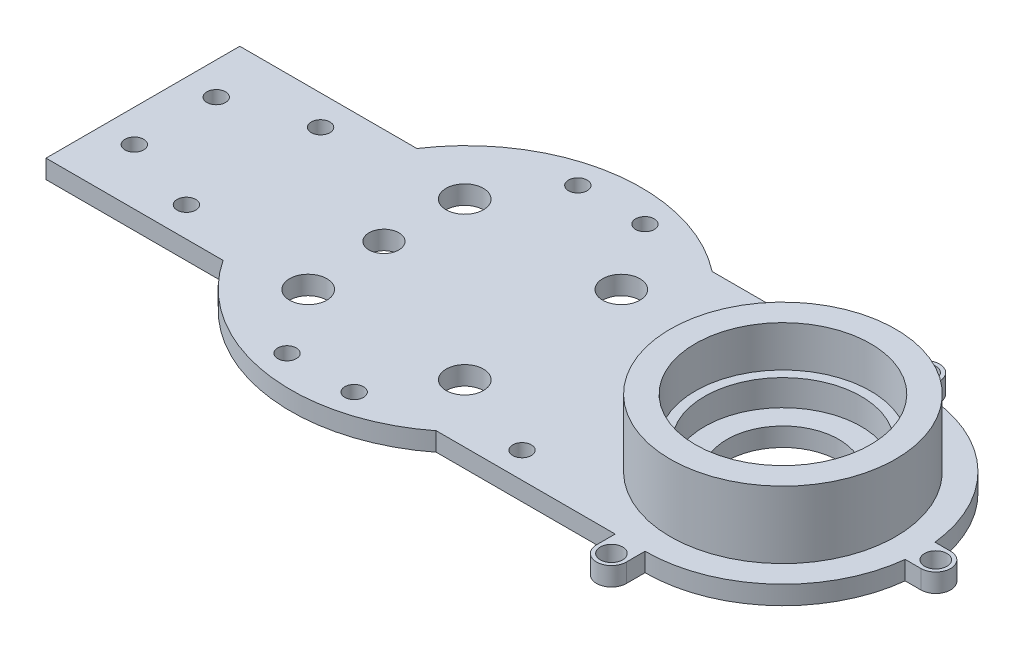
SolidWorks part; units mm, degrees
ref_plane "Front Plane" through (0, 0, 0) normal (0, 0, 1) x (1, 0, 0)
ref_plane "Top Plane" through (0, 0, 0) normal (0, 1, 0) x (1, 0, 0)
ref_plane "Right Plane" through (0, 0, 0) normal (1, 0, 0) x (0, 0, -1)
sketch "Sketch1" plane through (0, 0, 0) normal (0, 1, 0) x (1, 0, 0)
  line L0 (-72.9198, -40.4015) -> (-72.9198, 11.5785)
  line L1 (-72.9198, -40.4015) -> (-25.4198, -40.4015)
  line L2 (-72.9198, 11.5785) -> (-25.4198, 11.5785)
  line L3 (-72.9198, -40.4015) -> (-43.2498, -40.4015)
  line L12 (42.7452, 22.6085) -> (98.7452, 22.6085)
  line L13 (42.7502, -51.3915) -> (98.7452, -51.3915)
  line L14 (-72.9198, 11.5785) -> (-43.2498, 11.5785)
  line L22 (98.7452, 22.6085) -> (98.7452, 27.6085)
  line L23 (98.7452, -51.3915) -> (98.7452, -56.3899)
  line L24 (90.7452, 27.6085) -> (90.7452, 22.6085)
  line L25 (139.7485, -10.3958) -> (135.5288, -10.3958)
  line L26 (90.7452, -56.3899) -> (90.7452, -51.3915)
  line L28 (139.7485, -18.3872) -> (135.5288, -18.3872)
  arc A1 (-25.4198, 11.5785) -> (42.7452, 22.6085) centre (13.7566, -14.387) cw
  arc A3 (-25.4198, -40.4015) -> (42.7502, -51.3915) centre (13.7409, -14.4123) ccw
  arc A4 (98.7452, 22.6085) -> (98.7452, -51.3915) centre (98.7452, -14.3915) cw
  circle A5 centre (-64.25, -3.4086) radius 2.5
  circle A6 centre (-64.2198, -25.4086) radius 2.5
  circle A7 centre (-43.2498, -32.4115) radius 2.5
  circle A8 centre (-43.2498, 3.5885) radius 2.5
  circle A10 centre (4.7502, 24.5885) radius 2.5
  circle A11 centre (22.7502, 24.5885) radius 2.5
  circle A12 centre (4.7502, -53.4115) radius 2.5
  circle A13 centre (22.7502, -53.4115) radius 2.5
  circle A16 centre (58.7802, -44.4015) radius 2.5
  circle A17 centre (58.7802, 15.5785) radius 2.5106
  arc A18 (90.7452, 27.6085) -> (98.7452, 27.6085) centre (94.7452, 27.6085) cw
  circle A19 centre (94.7452, 27.6085) radius 3
  arc A20 (90.7452, -56.3899) -> (98.7452, -56.3899) centre (94.7452, -56.3899) ccw
  circle A21 centre (94.7452, -56.3899) radius 3
  circle A22 centre (139.7485, -14.3915) radius 3.0005
  arc A24 (139.7485, -10.3958) -> (139.7485, -18.3872) centre (139.7485, -14.3915) cw
  circle A28 centre (-8.2591, -14.4123) radius 4
  circle A30 centre (-7.25, 6.25) radius 5
  circle A31 centre (34.7501, 6.25) radius 4.9992
  circle A32 centre (-7.2499, -35.74) radius 5.0038
  circle A33 centre (34.7501, -35.73) radius 5
  dimension "D7" = 47
  dimension "D11" = 47
  dimension "D6" = 7.99
  dimension "D14" = 5
  dimension "D15" = 5
  dimension "D4" = 5
  dimension "D16" = 5
  dimension "D19" = 5
  dimension "D20" = 5
  dimension "D21" = 5
  dimension "D22" = 5
  dimension "D26" = 5
  dimension "D5" = 6
  dimension "D23" = 6
  dimension "D18" = 8
  dimension "D10" = 10
  dimension "D1" = 51.98
  dimension "D2" = 47.5
  dimension "D3" = 29.67
  dimension "D8" = 22
  dimension "D9" = 7.99
extrude "Boss-Extrude2" add sketch "Sketch1" along normal blind 5 contours A4 L12 A1 L2 L0 L1 A3 L13 A33 A32 A31 A30 A28 A17 A16 A13 A12 A11 A10 A8 A7 A6 A5 | L26 A20 L23 L13 A21 | A24 L25 A4 L28 A22 | A18 L24 L12 L22 A19
sketch "Sketch2" plane through (0, 5, 0) normal (0, 1, 0) x (1, 0, 0)
  circle A0 centre (98.7452, -14.3915) radius 15
  circle A1 centre (98.7452, -14.3915) radius 21
  circle A2 centre (98.7452, -14.3915) radius 23.5
extrude "Cut-Extrude1" cut sketch "Sketch2" against normal blind 7 contours A0
sketch "Sketch3" plane through (0, 5, 0) normal (0, 1, 0) x (1, 0, 0)
  circle A0 centre (98.7452, -14.3915) radius 21
  circle A1 centre (98.7452, -14.3915) radius 23.5
  dimension "D1" = 42
  dimension "D2" = 47
extrude "Boss-Extrude4" add sketch "Sketch3" along normal blind 7
sketch "Sketch4" plane through (0, 5, 0) normal (0, 1, 0) x (1, 0, 0)
  circle A0 centre (98.7452, -14.3915) radius 30.235
  circle M1 centre (98.7452, -14.3915) radius 23.5
  dimension "D1" = 60.47
extrude "Boss-Extrude5" add sketch "Sketch4" along normal blind 18 contours A0 M1
